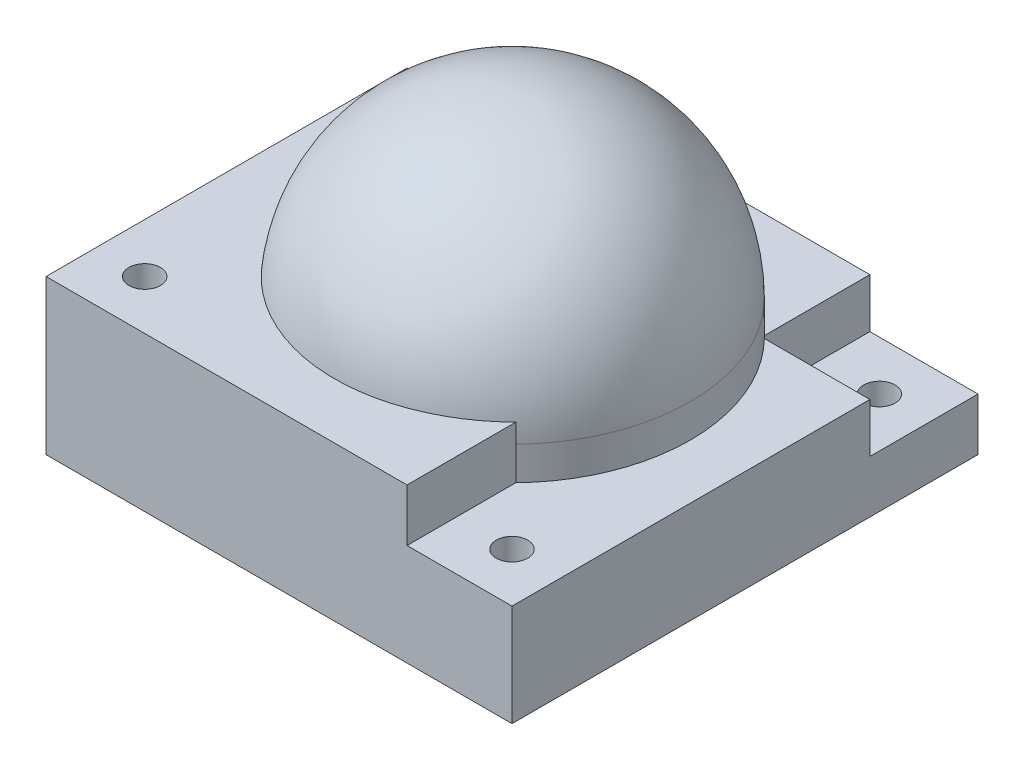
SolidWorks part; units mm, degrees
material "PET"
ref_plane "Front Plane" through (0, 0, 0) normal (0, 0, 1) x (1, 0, 0)
ref_plane "Top Plane" through (0, 0, 0) normal (0, 1, 0) x (1, 0, 0)
ref_plane "Right Plane" through (0, 0, 0) normal (1, 0, 0) x (0, 0, -1)
sketch "Sketch2" plane through (0, 0, 0) normal (0, 0, 1) x (1, 0, 0)
  line L0 (-10, 0) -> (-12, 0)
  line L1 (-17, 0) -> (-17, -3.175)
  line L2 (-17, -3.175) -> (-10, -3.175)
  line L3 (-10, -3.175) -> (-10, 0)
  line L4 (0, 12) -> (0, 17)
  arc A0 (0, 12) -> (-12, 0) centre (0, 0) ccw
  arc A1 (0, 17) -> (-17, 0) centre (0, 0) ccw
  dimension "D1" = 24
  dimension "D2" = 34
  dimension "D3" = 3.175
  dimension "D4" = 7
revolve "Revolve1" add sketch "Sketch2" angle 360 about L4
sketch "Sketch3" plane through (0, -3.175, 0) normal (0, -1, 0) x (1, 0, 0)
  line L1 (-22.2, 22.2) -> (22.2, 22.2)
  line L2 (-22.2, 22.2) -> (-22.2, -22.2)
  line L3 (-22.2, -22.2) -> (22.2, -22.2)
  line L4 (22.2, 22.2) -> (22.2, -22.2)
  circle A0 centre (0, 0) radius 10 construction
  dimension "D1" = 44.4
  dimension "D2" = 44.4
  dimension "D3" = 22.2
  dimension "D4" = 22.2
extrude "Boss-Extrude1" add sketch "Sketch3" along normal blind 9.7
sketch "Sketch4" plane through (0, -12.875, 0) normal (0, -1, 0) x (1, 0, 0)
  line L1 (22.2, -22.2) -> (11.9, -22.2)
  line L2 (22.2, -22.2) -> (22.2, -11.9)
  line L3 (22.2, -11.9) -> (11.9, -11.9)
  line L4 (11.9, -22.2) -> (11.9, -11.9)
  dimension "D1" = 10.3
  dimension "D2" = 10.3
sketch "Sketch5" plane through (0, -12.875, 0) normal (0, -1, 0) x (1, 0, 0)
  line L0 (-22.2, -22.2) -> (22.2, -22.2) construction
  line L1 (22.2, -22.2) -> (22.2, 22.2) construction
  circle A0 centre (0, 0) radius 6
  dimension "D1" = 22.2
  dimension "D2" = 22.2
  dimension "D3" = 12
extrude "Cut-Extrude2" cut sketch "Sketch5" against normal blind 14.3
sketch "Sketch6" plane through (0, -3.175, 0) normal (0, 1, 0) x (1, 0, 0)
  line L0 (-22.2, -22.2) -> (-22.2, 12.2)
  line L1 (-22.2, -22.2) -> (-22.2, 22.2) construction
  line L2 (-22.2, -22.2) -> (12.2, -22.2)
  line L3 (22.2, -22.2) -> (-22.2, -22.2) construction
  line L6 (12.2, -22.2) -> (12.2, -11.83)
  line L7 (-22.2, 12.2) -> (-11.83, 12.2)
  arc A2 (12.2, -11.83) -> (-11.83, 12.2) centre (0.185, 0.185) cw
  dimension "D1" = 34.4
  dimension "D2" = 34.4
  dimension "D3" = 10.37
  dimension "D4" = 10.37
extrude "Boss-Extrude2" add sketch "Sketch6" along normal blind 5
sketch "Sketch7" plane through (0, 1.825, 0) normal (0, 1, 0) x (1, 0, 0)
  line L0 (22.2, 22.2) -> (22.2, -22.2) construction
  line L1 (-22.2, 22.2) -> (22.2, 22.2) construction
  line L2 (-22.2, 12.2) -> (-22.2, 22.2) construction
  line L3 (-22.2, 12.2) -> (-22.2, -22.2) construction
  line L4 (-22.2, -22.2) -> (12.2, -22.2) construction
  line L5 (22.2, -22.2) -> (12.2, -22.2) construction
  circle A0 centre (-17.5, -17.5) radius 1.5
  circle A1 centre (17.5, -17.5) radius 1.5
  circle A2 centre (17.5, 17.5) radius 1.5
  circle A3 centre (-17.5, 17.5) radius 1.5
  dimension "D1" = 3
  dimension "D2" = 3
  dimension "D3" = 3
  dimension "D4" = 3
  dimension "D5" = 4.7
  dimension "D6" = 4.7
  dimension "D7" = 4.7
  dimension "D8" = 4.7
  dimension "D9" = 4.7
  dimension "D10" = 4.7
  dimension "D11" = 4.7
  dimension "D12" = 4.7
extrude "Cut-Extrude3" cut sketch "Sketch7" against normal through all both and the other way through all
sketch "Sketch8" plane through (0, -3.175, 0) normal (0, 1, 0) x (1, 0, 0)
  line L1 (22.2, 22.2) -> (11.9, 22.2)
  line L2 (22.2, 22.2) -> (22.2, 11.9)
  line L3 (22.2, 11.9) -> (11.9, 11.9)
  line L4 (11.9, 22.2) -> (11.9, 11.9)
  dimension "D1" = 10.3
  dimension "D2" = 10.3
extrude "Cut-Extrude4" cut sketch "Sketch8" against normal blind 4.7
